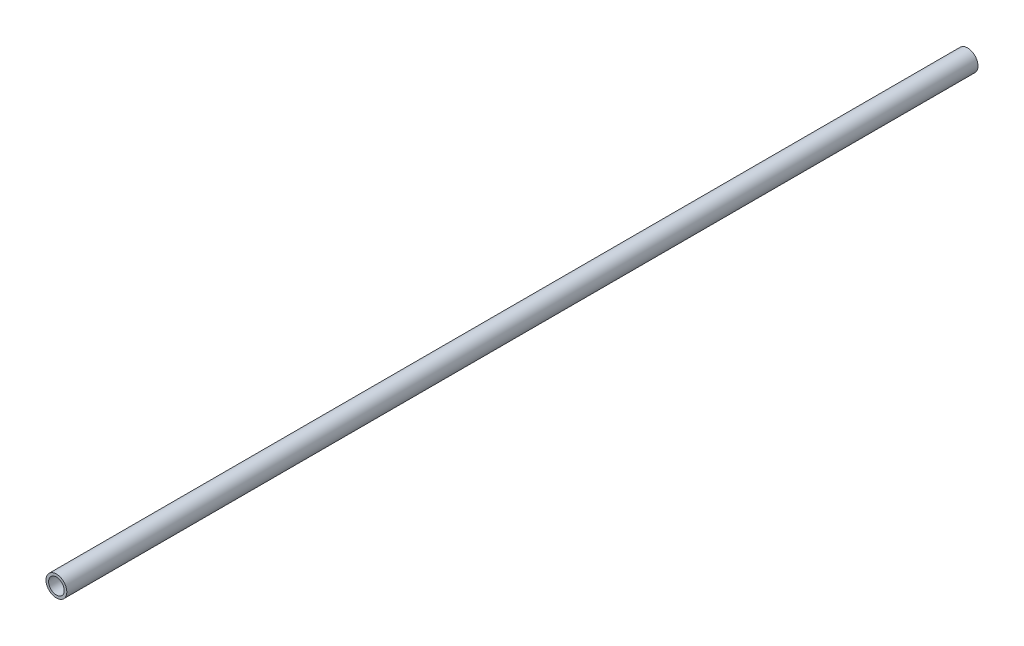
SolidWorks part; units mm, degrees
material "Thornel Mat VMA"
ref_plane "前视基准面" through (0, 0, 0) normal (0, 0, 1) x (1, 0, 0)
ref_plane "上视基准面" through (0, 0, 0) normal (0, 1, 0) x (1, 0, 0)
ref_plane "右视基准面" through (0, 0, 0) normal (1, 0, 0) x (0, 0, -1)
sketch "草图1" plane through (0, 0, 0) normal (0, 0, 1) x (1, 0, 0)
  circle A0 centre (0, 0) radius 4
  circle A1 centre (0, 0) radius 3
  dimension "D1" = 8
  dimension "D2" = 6
extrude "凸台-拉伸1" add sketch "草图1" along normal blind 350
